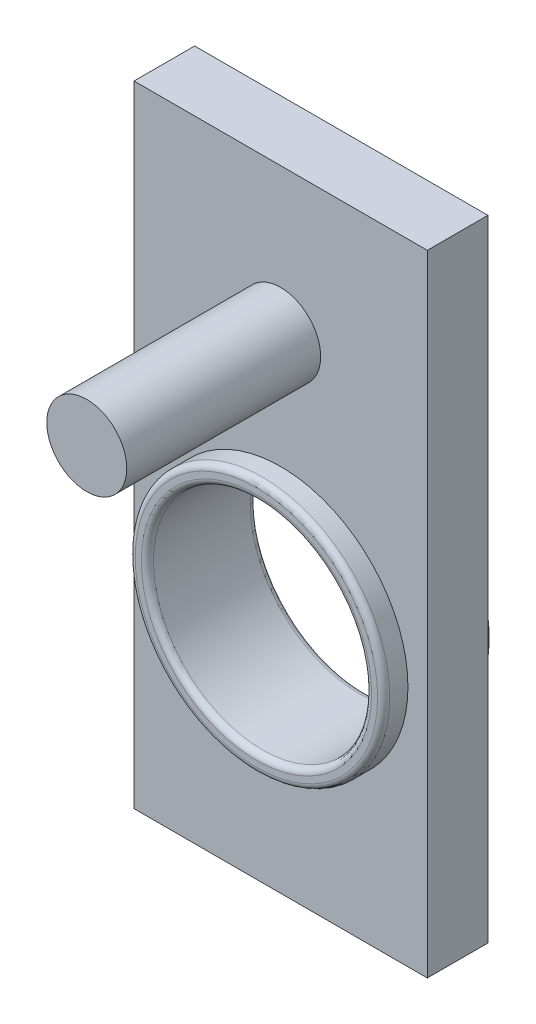
SolidWorks part; units mm, degrees
ref_plane "Спереди" through (0, 0, 0) normal (0, 0, 1) x (1, 0, 0)
ref_plane "Сверху" through (0, 0, 0) normal (0, 1, 0) x (1, 0, 0)
ref_plane "Справа" through (0, 0, 0) normal (1, 0, 0) x (0, 0, -1)
sketch "Эскиз1" plane through (0, 0, 0) normal (0, 0, 1) x (1, 0, 0)
  line L0 (0, 30.9521) -> (0, -24.4025) construction
  line L1 (-18.8037, 0) -> (18.3811, 0) construction
  line L3 (-6.05, -10) -> (6.05, -10)
  line L4 (-6.05, -10) -> (-6.05, 16)
  line L5 (-6.05, 16) -> (6.05, 16)
  line L6 (6.05, -10) -> (6.05, 16)
  circle A0 centre (0, 0) radius 4.5
  dimension "D2" = 9
  dimension "D1" = 12.1
  dimension "D3" = 16
  dimension "D4" = 10
extrude "Вытянуть1" add sketch "Эскиз1" along normal blind 2.5
sketch "Эскиз2" plane through (0, 0, 2.5) normal (0, 0, 1) x (1, 0, 0)
  line L0 (0, 0) -> (0, 13.0454) construction
  circle A0 centre (0, 10) radius 1.65
  circle A1 centre (0, 0) radius 4.5 construction
  dimension "D1" = 3.3
  dimension "D2" = 10
extrude "Вытянуть2" add sketch "Эскиз2" along normal blind 8
sketch "Эскиз3" plane through (0, 0, 2.5) normal (0, 0, 1) x (1, 0, 0)
  circle A0 centre (0, 0) radius 4.5 construction
  circle A1 centre (0, 0) radius 4.5
  circle A2 centre (0, 0) radius 5.25
  dimension "D1" = 10.5
extrude "Вытянуть3" add sketch "Эскиз3" along normal blind 1 and the other way blind 3.5
fillet "Скругление1" radius 0.25 4 edges at (5.25, 0, 3.5) (5.25, 0, -1) (4.5, 0, -1) (4.5, 0, 3.5)
